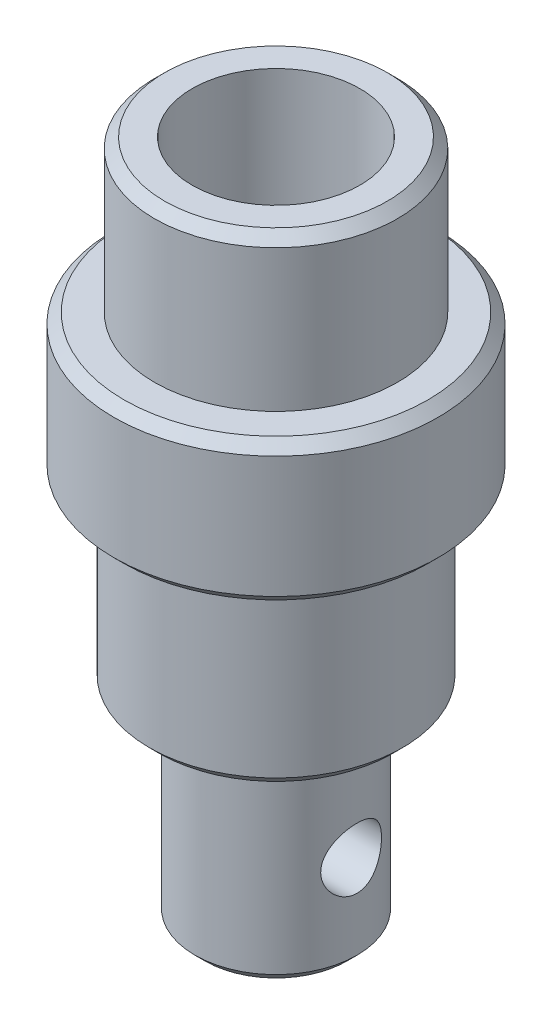
SolidWorks part; units mm, degrees
material "AISI 4130 Steel, normalized at 870C"
ref_plane "Front Plane" through (0, 0, 0) normal (0, 0, 1) x (1, 0, 0)
ref_plane "Top Plane" through (0, 0, 0) normal (0, 1, 0) x (1, 0, 0)
ref_plane "Right Plane" through (0, 0, 0) normal (1, 0, 0) x (0, 0, -1)
sketch "Sketch1" plane through (0, 0, 0) normal (0, 1, 0) x (1, 0, 0)
  circle A0 centre (0, 0) radius 12.5
  dimension "D1" = 25
extrude "Boss-Extrude1" add sketch "Sketch1" along normal blind 67
sketch "Sketch14" plane through (0, 67, 0) normal (0, 1, 0) x (1, 0, 0)
  circle A0 centre (0, 0) radius 16
  dimension "D1" = 32
extrude "Boss-Extrude2" add sketch "Sketch14" against normal blind 29
sketch "Sketch3" plane through (0, 0, 0) normal (0, -1, 0) x (1, 0, 0)
  circle A0 centre (0, 0) radius 10.5
  dimension "D1" = 21
sketch "Sketch4" plane through (0, 67, 0) normal (0, 1, 0) x (1, 0, 0)
  circle A1 centre (0, 0) radius 8.2804
  dimension "D1" = 16.5608
extrude "Cut-Extrude2" cut sketch "Sketch4" against normal blind 18
ref_plane "Plane1" through (0, 0, 15) normal (0, 0, 1) x (1, 0, 0)
sketch "Sketch8" plane through (0, 67, 0) normal (0, 1, 0) x (1, 0, 0)
  circle A0 centre (0, 0) radius 12
  dimension "D1" = 24
extrude "Cut-Extrude4" cut sketch "Sketch8" against normal blind 15 flip side to cut
chamfer "Chamfer1" distance 1 angle 45 2 edges at (0, 52, 16) (0, 38, 16)
sketch "Sketch25" plane through (0, 0, 0) normal (0, -1, 0) x (1, 0, 0)
  circle A0 centre (0, 0) radius 8
  dimension "D1" = 16
extrude "Cut-Extrude7" cut sketch "Sketch25" against normal blind 20 flip side to cut
chamfer "Chamfer2" distance 1 angle 45 3 edges at (0, 0, -8) (0, 20, -12.5) (0, 67, 12)
sketch "Sketch26" plane through (0, 0, 0) normal (1, 0, 0) x (0, 0, -1)
  line L0 (-11.5, 20) -> (11.5, 20) construction
  circle A0 centre (0, 9.3) radius 3
  dimension "D2" = 6
  dimension "D1" = 10.7
extrude "Cut-Extrude8" cut sketch "Sketch26" against normal through all both and the other way through all contours A0
